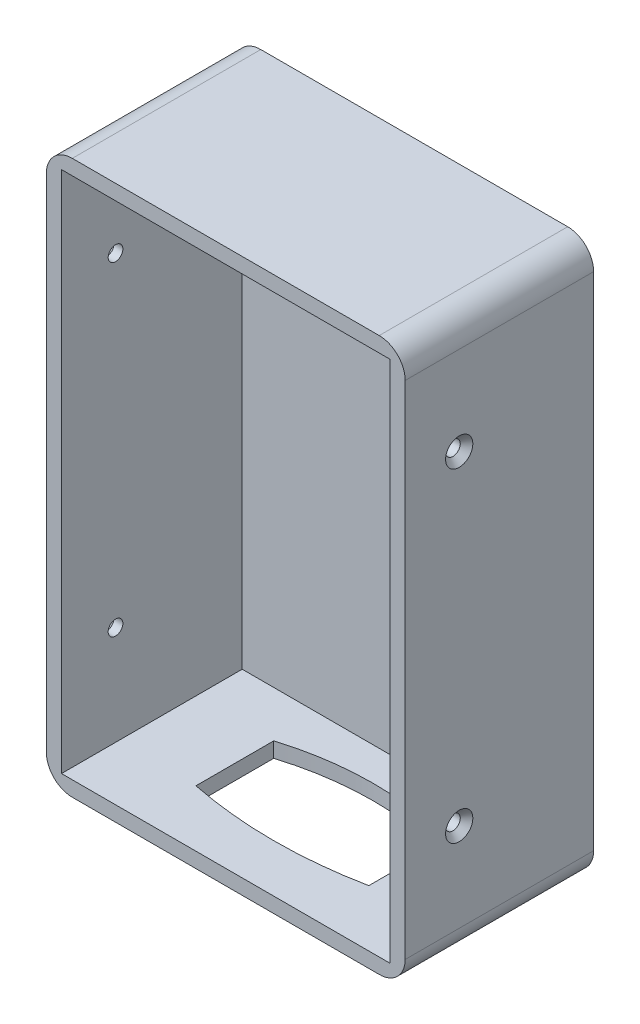
SolidWorks part; units mm, degrees
ref_plane "Přední rovina" through (0, 0, 0) normal (0, 0, 1) x (1, 0, 0)
ref_plane "Horní rovina" through (0, 0, 0) normal (0, 1, 0) x (1, 0, 0)
ref_plane "Pravá rovina" through (0, 0, 0) normal (1, 0, 0) x (0, 0, -1)
sketch "Skica1" plane through (0, 0, 0) normal (0, 0, 1) x (1, 0, 0)
  line L0 (-41.5, 58) -> (-41.5, -58)
  line L1 (-38, 60.5) -> (38, 60.5)
  line L2 (-38, 60.5) -> (-38, -60.5)
  line L3 (-38, -60.5) -> (38, -60.5)
  line L4 (38, 60.5) -> (38, -60.5)
  line L5 (-38, 60.5) -> (38, -60.5) construction
  line L6 (-38, -60.5) -> (38, 60.5) construction
  line L7 (-35.5, -64) -> (35.5, -64)
  line L8 (41.5, 58) -> (41.5, -58)
  line L9 (-35.5, 64) -> (35.5, 64)
  line L10 (-41.5, 64) -> (-41.5, -64) construction
  line L11 (-41.5, -64) -> (41.5, -64) construction
  line L12 (41.5, 64) -> (41.5, -64) construction
  line L13 (-41.5, 64) -> (41.5, 64) construction
  arc A0 (-41.5, -58) -> (-35.5, -64) centre (-35.5, -58) ccw
  arc A1 (35.5, -64) -> (41.5, -58) centre (35.5, -58) ccw
  arc A2 (41.5, 58) -> (35.5, 64) centre (35.5, 58) ccw
  arc A3 (-41.5, 58) -> (-35.5, 64) centre (-35.5, 58) cw
  point P0 (0, 0)
  dimension "D4" = 6
  dimension "D1" = 76
  dimension "D2" = 121
  dimension "D3" = 3.5
extrude "Přidat vysunutím1" add sketch "Skica1" along normal blind 43.6
sketch "Skica2" plane through (0, 0, 0) normal (0, 0, -1) x (-1, 0, 0)
  line L1 (38, 60.5) -> (-38, 60.5)
  line L2 (38, 60.5) -> (38, -60.5)
  line L3 (38, -60.5) -> (-38, -60.5)
  line L4 (-38, 60.5) -> (-38, -60.5)
  line L5 (38, 60.5) -> (-38, -60.5) construction
  line L6 (38, -60.5) -> (-38, 60.5) construction
  point P0 (0, 0)
extrude "Přidat vysunutím2" add sketch "Skica2" against normal blind 1.8
sketch "Skica3" plane through (0, -64, 0) normal (0, -1, 0) x (1, 0, 0)
  line L0 (0, 0) -> (0, 9.5)
  line L1 (0, 9.5) -> (20, 9.5)
  line L2 (20, 9.5) -> (20, 32.5)
  line L3 (20, 32.5) -> (-20, 32.5)
  line L4 (-20, 32.5) -> (-20, 9.5)
  line L5 (-20, 9.5) -> (0, 9.5)
  line L6 (0, 9.5) -> (0, 32.5)
  arc A0 (-20, 30.5) -> (20, 30.5) centre (0, -68.5) cw
  arc A1 (-20, 12.5) -> (20, 12.5) centre (0, 77.6667) ccw
  point P3 (-20, 12.5)
  point P8 (20, 12.5)
  point P9 (20, 30.5)
  point P10 (-20, 30.5)
  dimension "D1" = 9.5
  dimension "D2" = 20
  dimension "D3" = 23
  dimension "D4" = 3
  dimension "D5" = 3
  dimension "D6" = 2
  dimension "D7" = 2
extrude "Odebrat vysunutím1" cut sketch "Skica3" against normal up to next contours L4 A1 L6 A0 | L6 A1 L2 A0
sketch "Skica4" plane through (41.5, 0, 0) normal (1, 0, 0) x (0, 0, -1)
  line L0 (-31.1, 58) -> (-31.1, -58)
  line L1 (-43.6, 58) -> (0, 58) construction
  line L2 (-43.6, -58) -> (0, -58) construction
  line L3 (-31.1, 0) -> (0, 0)
  line L4 (0, -58) -> (0, 58) construction
  point P6 (-31.1, -37.5)
  point P7 (-31.1, 37.5)
  dimension "D1" = 12.5
  dimension "D2" = 37.5
  dimension "D3" = 37.5
hole_wizard "Kuželové zahloubení pro M3 šroubu se zápustnou hlavou plochou1" positions "Skica5" profile "Skica6" countersink size "M3" standard "DIN"
sketch "Skica5" plane through (41.5, 0, 0) normal (1, 0, 0) x (0, 0, -1)
  point P0 (-31.1, -37.5)
  point P3 (-31.1, 37.5)
sketch "Skica6" plane through (41.5, -37.5, 31.1) normal (0, 1, 0) x (0, 0, -1)
  line L0 (0, 0) -> (0, 83)
  line L1 (0, 83) -> (1.7, 83)
  line L2 (1.7, 83) -> (1.7, 1.45)
  line L3 (1.7, 1.45) -> (3.15, 0)
  line L5 (3.15, 0) -> (0, 0)
  line L6 (-1.7, 1.45) -> (-3.15, 0) construction
  line L11 (0, -6.35) -> (0, 107.95) construction
  dimension "Průměr díry skrz" = 3.4
  dimension "Hloubka díry skrz" = 83
  dimension "Průměr blíz. kuž. zahloubení" = 6.3
  dimension "Úhel blíz. kuž. zahloubení" = 90
ref_plane "Rovina1" through (0, 0, 0) normal (1, 0, 0) x (0, 0, -1)
mirror "Zrcadlit1" about plane through (0, 0, 0) normal (1, 0, 0) of "Kuželové zahloubení pro M3 šroubu se zápustnou hlavou plochou1"
sketch "Skica7" plane through (0, 0, 0) normal (0, 0, -1) x (-1, 0, 0)
  line L0 (0, 64) -> (0, 49)
  line L1 (-35.5, 64) -> (35.5, 64) construction
  line L3 (-8, 54) -> (8, 54)
  line L4 (-10, 52) -> (-10, 46)
  line L5 (-8, 44) -> (8, 44)
  line L6 (10, 52) -> (10, 46)
  line L7 (-10, 54) -> (10, 44) construction
  line L8 (-10, 44) -> (10, 54) construction
  arc A0 (8, 44) -> (10, 46) centre (8, 46) ccw
  arc A1 (8, 54) -> (10, 52) centre (8, 52) cw
  arc A2 (-8, 54) -> (-10, 52) centre (-8, 52) ccw
  arc A3 (-10, 46) -> (-8, 44) centre (-8, 46) ccw
  dimension "D4" = 2
  dimension "D1" = 15
  dimension "D2" = 20
  dimension "D3" = 10
extrude "Odebrat vysunutím2" cut sketch "Skica7" against normal through all contours L5 A0 L6 A1 L3 A2 L4 A3
